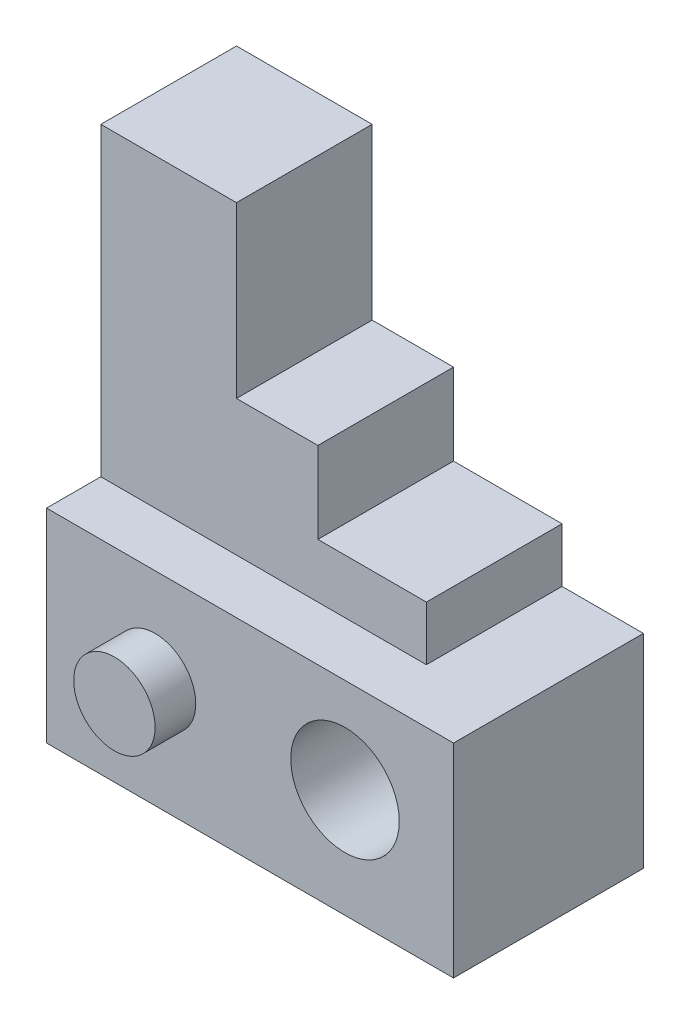
SolidWorks part; units mm, degrees
material "Aluminum Bronze"
ref_plane "Front Plane" through (0, 0, 0) normal (0, 0, 1) x (1, 0, 0)
ref_plane "Top Plane" through (0, 0, 0) normal (0, 1, 0) x (1, 0, 0)
ref_plane "Right Plane" through (0, 0, 0) normal (1, 0, 0) x (0, 0, -1)
sketch "Sketch1" plane through (0, 0, 0) normal (0, 0, 1) x (1, 0, 0)
  line L1 (0, 0) -> (60, 0)
  line L2 (0, 0) -> (0, 30)
  line L3 (0, 30) -> (60, 30)
  line L4 (60, 0) -> (60, 30)
  circle A0 centre (44, 16) radius 8
  dimension "D3" = 16
  dimension "D1" = 60
  dimension "D2" = 30
  dimension "D4" = 16
  dimension "D5" = 16
extrude "Boss-Extrude1" add sketch "Sketch1" along normal blind 28
sketch "Sketch2" plane through (0, 0, 0) normal (0, 0, 1) x (1, 0, 0)
  line L0 (0, 30) -> (0, 75)
  line L1 (0, 75) -> (20, 75)
  line L2 (20, 75) -> (20, 50)
  line L3 (20, 50) -> (32, 50)
  line L4 (32, 50) -> (32, 38)
  line L5 (32, 38) -> (48, 38)
  line L6 (48, 38) -> (48, 30)
  line L7 (60, 30) -> (0, 30) construction
  line L8 (48, 30) -> (0, 30)
  line L9 (0, 0) -> (60, 0) construction
  line L10 (60, 0) -> (60, 30) construction
  dimension "D1" = 75
  dimension "D2" = 12
  dimension "D3" = 12
  dimension "D4" = 12
  dimension "D5" = 20
  dimension "D6" = 20
extrude "Boss-Extrude2" add sketch "Sketch2" along normal blind 20
sketch "Sketch3" plane through (0, 0, 28) normal (0, 0, 1) x (1, 0, 0)
  line L0 (0, 0) -> (60, 0) construction
  line L1 (0, 0) -> (0, 30) construction
  circle A0 centre (16, 16) radius 6
  dimension "D3" = 12
  dimension "D1" = 16
  dimension "D2" = 16
extrude "Boss-Extrude3" add sketch "Sketch3" along normal blind 6
